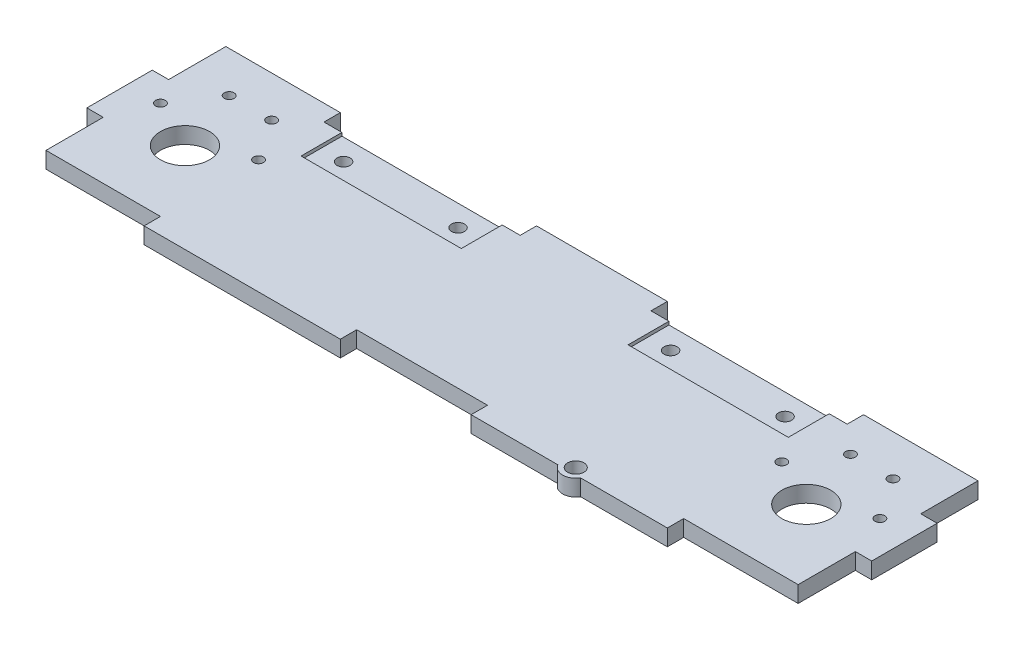
SolidWorks part; units mm, degrees
ref_plane "Plan de face" through (0, 0, 0) normal (0, 0, 1) x (1, 0, 0)
ref_plane "Plan de dessus" through (0, 0, 0) normal (0, 1, 0) x (1, 0, 0)
ref_plane "Plan de droite" through (0, 0, 0) normal (1, 0, 0) x (0, 0, -1)
sketch "Esquisse2" plane through (0, 0, 0) normal (0, 1, 0) x (1, 0, 0)
  line L0 (-75.2145, -31.3914) -> (-75.2145, -26.3914)
  line L1 (-110.2145, 28.6086) -> (-75.2145, 28.6086)
  line L2 (-115.2145, 11.1086) -> (-115.2145, -8.8914)
  line L3 (-75.2145, -31.3914) -> (-15.2145, -31.3914)
  line L4 (124.7855, 11.1086) -> (124.7855, -8.8914)
  line L5 (-75.2145, 28.6086) -> (-75.2145, 23.6086)
  line L6 (-75.2145, 23.6086) -> (-15.2145, 23.6086)
  line L7 (-75.2145, -26.3914) -> (-110.2145, -26.3914)
  line L8 (-15.2145, -31.3914) -> (-15.2145, -26.3914)
  line L9 (-15.2145, -26.3914) -> (24.7855, -26.3914)
  line L10 (24.7855, -26.3914) -> (24.7855, -31.3914)
  line L11 (84.7855, -31.3914) -> (84.7855, -26.3914)
  line L12 (84.7855, -26.3914) -> (119.7855, -26.3914)
  line L13 (24.7855, -31.3914) -> (84.7855, -31.3914)
  line L14 (99.7855, -3.8914) -> (99.7855, 23.6086) construction
  line L15 (114.7855, 20.1843) -> (114.7855, -1.3914) construction
  line L16 (99.7855, 3.6086) -> (129.7855, 3.6086) construction
  line L17 (106.2855, 24.9898) -> (106.2855, 7.2273) construction
  line L18 (4.7855, 28.6086) -> (4.7855, -24.6414) construction
  line L19 (124.7855, -8.8914) -> (119.7855, -8.8914)
  line L20 (-110.2145, 11.1086) -> (-110.2145, 28.6086)
  line L21 (119.7855, 11.1086) -> (124.7855, 11.1086)
  line L22 (119.7855, -8.8914) -> (119.7855, -26.3914)
  line L23 (119.7855, 11.1086) -> (119.7855, 28.6086)
  line L24 (-110.2145, -8.8914) -> (-110.2145, -26.3914)
  line L25 (-110.2145, 11.1086) -> (-115.2145, 11.1086)
  line L26 (-115.2145, -8.8914) -> (-110.2145, -8.8914)
  line L27 (-115.1149, -26.3914) -> (-115.2145, -26.3914)
  line L28 (-15.2145, 23.6086) -> (-15.2145, 28.6086)
  line L29 (24.7855, 28.6086) -> (24.7855, 23.6086)
  line L30 (24.7855, 23.6086) -> (84.7855, 23.6086)
  line L31 (84.7855, 23.6086) -> (84.7855, 28.6086)
  line L32 (-15.2145, 28.6086) -> (24.7855, 28.6086)
  line L33 (84.7855, 28.6086) -> (119.7855, 28.6086)
  circle A0 centre (99.7855, -3.8914) radius 7.5
  circle A1 centre (114.7855, 3.6086) radius 1.5
  circle A2 centre (106.2855, 16.1086) radius 1.5
  circle A3 centre (93.2855, 16.1086) radius 1.5
  circle A4 centre (84.7855, 3.6086) radius 1.5
  circle A5 centre (54.7855, -29.3914) radius 4
  circle A6 centre (54.7855, -29.3914) radius 2.5
  circle A9 centre (-105.2145, 3.6086) radius 1.5
  circle A10 centre (-96.7145, 16.1086) radius 1.5
  circle A11 centre (-83.7145, 16.1086) radius 1.5
  circle A12 centre (-75.2145, 3.6086) radius 1.5
  circle A13 centre (-90.2145, -3.8914) radius 7.5
  point P0 (0, 0)
  dimension "D7" = 15
  dimension "D9" = 15
  dimension "D10" = 3
  dimension "D11" = 3
  dimension "D15" = 2
  dimension "D16" = 5
  dimension "D17" = 8
  dimension "D18" = 20
  dimension "D2" = 5
  dimension "D3" = 35
  dimension "D4" = 40
  dimension "D5" = 60
  dimension "D6" = 60
  dimension "D8" = 22.5
  dimension "D12" = 12.5
  dimension "D13" = 6.5
  dimension "D14" = 25
  dimension "D19" = 17.5
  dimension "D20" = 17.5
  dimension "D21" = 35
  dimension "D22" = 5
  dimension "D23" = 5
  dimension "D24" = 30
  dimension "D25" = 5
  dimension "D26" = 60
  dimension "D27" = 5
extrude "Boss.-Extru.5" add sketch "Esquisse2" along normal blind 5 contours A5 L13 L11 L12 L22 L19 L4 L21 L23 L1 L20 L25 L2 L26 L24 L7 L0 L3 L8 L9 L10 A10 A4 A0 A1 A2 A3 A9 A11 A12 A13 | A6 L13 A5 | A6 L13 A5
sketch "Esquisse3" plane through (0, 5, 0) normal (0, 1, 0) x (1, 0, 0)
  line L0 (30.2855, 23.6086) -> (30.2855, 11.1086)
  line L1 (24.7855, 23.6086) -> (84.7855, 23.6086) construction
  line L2 (79.2855, 23.6086) -> (79.2855, 11.1086)
  line L3 (79.2855, 11.1086) -> (30.2855, 11.1086)
  line L4 (79.2855, 23.6086) -> (30.2855, 23.6086)
  line L5 (4.7855, -26.3914) -> (4.7855, 59.2916) construction
  line L6 (-15.2145, -26.3914) -> (24.7855, -26.3914) construction
  line L7 (-69.7145, 23.6086) -> (-69.7145, 11.1086)
  line L8 (-69.7145, 11.1086) -> (-20.7145, 11.1086)
  line L9 (-20.7145, 23.6086) -> (-20.7145, 11.1086)
  line L10 (-69.7145, 23.6086) -> (-20.7145, 23.6086)
  dimension "D1" = 49
  dimension "D2" = 5.5
  dimension "D3" = 12.5
extrude "Enlèv. mat.-Extru.1" cut sketch "Esquisse3" against normal blind 1 contours L4 L0 L3 L2 | L7 L8 L9 L10
sketch "Esquisse4" plane through (0, 5, 0) normal (0, 1, 0) x (1, 0, 0)
  line L0 (79.2855, 23.6086) -> (79.2855, 11.1086) construction
  line L1 (79.2855, 11.1086) -> (30.2855, 11.1086) construction
  line L2 (4.7855, -26.3914) -> (4.7855, 57.4812) construction
  line L4 (-15.2145, -26.3914) -> (24.7855, -26.3914) construction
  circle A0 centre (72.2855, 17.1086) radius 2
  circle A1 centre (37.2855, 17.1086) radius 2
  circle A2 centre (-27.7145, 17.1086) radius 2
  circle A3 centre (-62.7145, 17.1086) radius 2
  dimension "D1" = 4
  dimension "D2" = 7
  dimension "D3" = 6
extrude "Enlèv. mat.-Extru.2" cut sketch "Esquisse4" against normal through all
